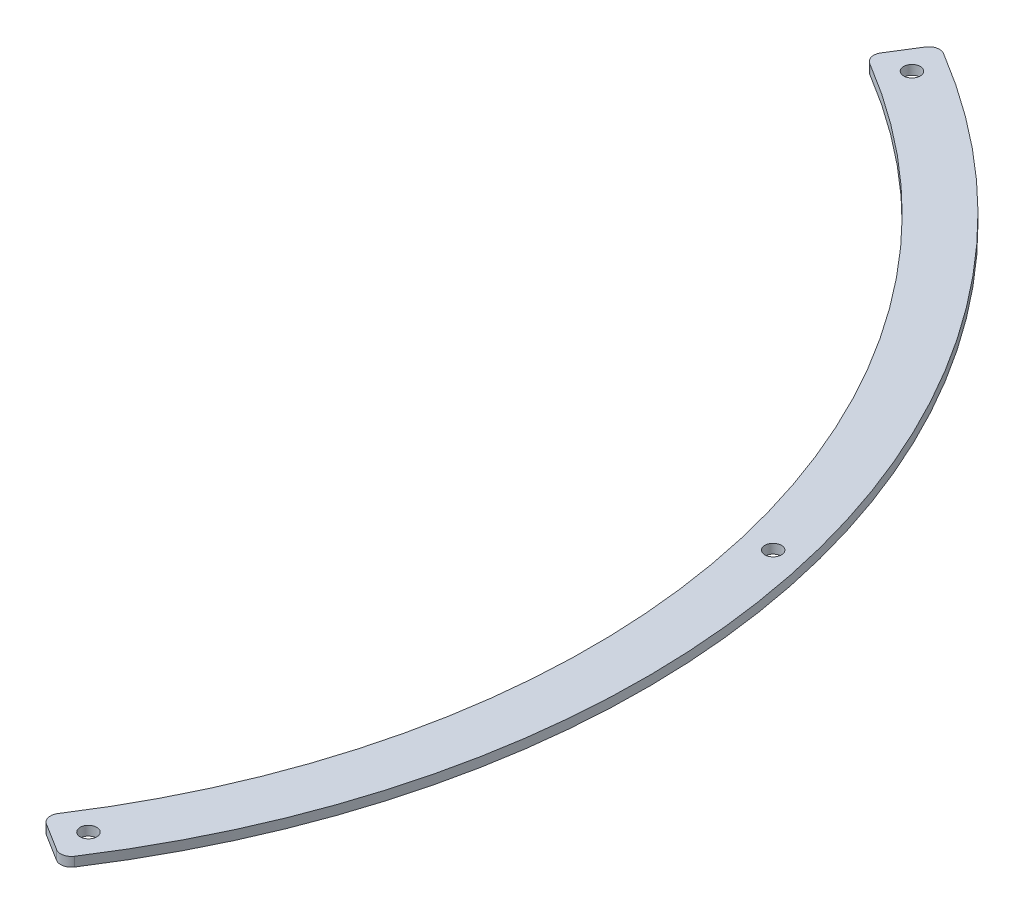
SolidWorks part; units mm, degrees
ref_plane "Front Plane" through (0, 0, 0) normal (0, 0, 1) x (1, 0, 0)
ref_plane "Top Plane" through (0, 0, 0) normal (0, 1, 0) x (1, 0, 0)
ref_plane "Right Plane" through (0, 0, 0) normal (1, 0, 0) x (0, 0, -1)
sketch "Sketch1" plane through (0, 0, 0) normal (0, 1, 0) x (1, 0, 0)
  line L0 (139.4673, 12.2018) -> (149.4292, 13.0734) construction
  line L1 (74.1887, 118.7267) -> (79.4879, 127.2072) construction
  line L2 (118.7267, -74.1887) -> (127.2072, -79.4879) construction
  line L3 (140, 0) -> (191.8044, 0) construction
  line L6 (70.9915, 123.0455) -> (74.1717, 128.1349)
  line L8 (117.7464, -79.472) -> (122.8357, -82.6522)
  arc A0 (117.1329, -76.6804) -> (117.7464, -79.472) centre (118.8062, -77.7759) ccw
  arc A1 (117.1329, -76.6804) -> (71.6638, 120.2676) centre (0, 0) ccw
  arc A2 (125.5698, -82.0501) -> (76.893, 128.7923) centre (0, 0) ccw
  arc A3 (71.6638, 120.2676) -> (70.9915, 123.0455) centre (72.6876, 121.9857) cw
  arc A6 (122.8357, -82.6522) -> (125.5698, -82.0501) centre (123.8956, -80.9561) ccw
  arc A10 (74.1717, 128.1349) -> (76.893, 128.7923) centre (75.8678, 127.0751) cw
  dimension "D1" = 10
  dimension "D11" = 140
  dimension "D12" = 2
  dimension "D5" = 2
  dimension "D2" = 5
  dimension "D3" = 5
  dimension "D4" = 32
extrude "Boss-Extrude1" add sketch "Sketch1" along normal blind 1.75
sketch "Sketch2" plane through (0, 1.75, 0) normal (0, 1, 0) x (1, 0, 0)
  line L0 (0, 0) -> (85.7967, 137.3034) construction
  line L1 (0, 0) -> (175.3344, 40.4791) construction
  line L2 (0, 0) -> (150.2013, -93.8562) construction
  line L3 (23.0028, -8.4778) -> (119.5296, -68.7945) construction
  line L4 (22.2601, 10.2707) -> (133.1652, 35.8751) construction
  line L5 (77.275, 114.2304) -> (16.9583, 17.7036) construction
  circle A7 centre (122.967, -76.8383) radius 1.55
  circle A8 centre (141.2837, 32.6179) radius 1.55
  circle A11 centre (76.8383, 122.967) radius 1.55
  dimension "D9" = 145
  dimension "D10" = 145
  dimension "D11" = 145
extrude "Mounting_Holes" cut sketch "Sketch2" against normal up to next
equation "\"d1\"= 1cm"
equation "\"D2@Sketch1\"=\"d1\"/2"
equation "\"D6@Sketch1\"=\"d1\"/2"
equation "\"D7@Sketch1\"=\"d1\""
equation "\"D8@Sketch1\"=\"d1\"/2"
equation "\"D9@Sketch1\"=\"d1\""
equation "\"D1@Sketch1\"=\"d1\""
equation "\"r1\"= 23mm"
equation "\"r2\"= 14cm"
equation "\"D11@Sketch1\"=\"r2\""
equation "\"D10@Sketch1\"=\"r1\""
equation "\"D3@Sketch2\"=13+4.4+1.55"
equation "\"D5@Sketch2\"=11.2+4.4+1.55"
equation "\"D6@Sketch2\"=(\"r2\"+\"r1\")/2"
equation "\"D7@Sketch2\"=\"D6@Sketch2\""
equation "\"D8@Sketch2\"=\"D6@Sketch2\""
equation "\"D9@Sketch2\"=\"r2\"+\"d1\"/2"
equation "\"D10@Sketch2\"=\"D9@Sketch2\""
equation "\"D11@Sketch2\"=\"D9@Sketch2\""
equation "\"D3@Sketch1\"=\"D2@Sketch1\""
